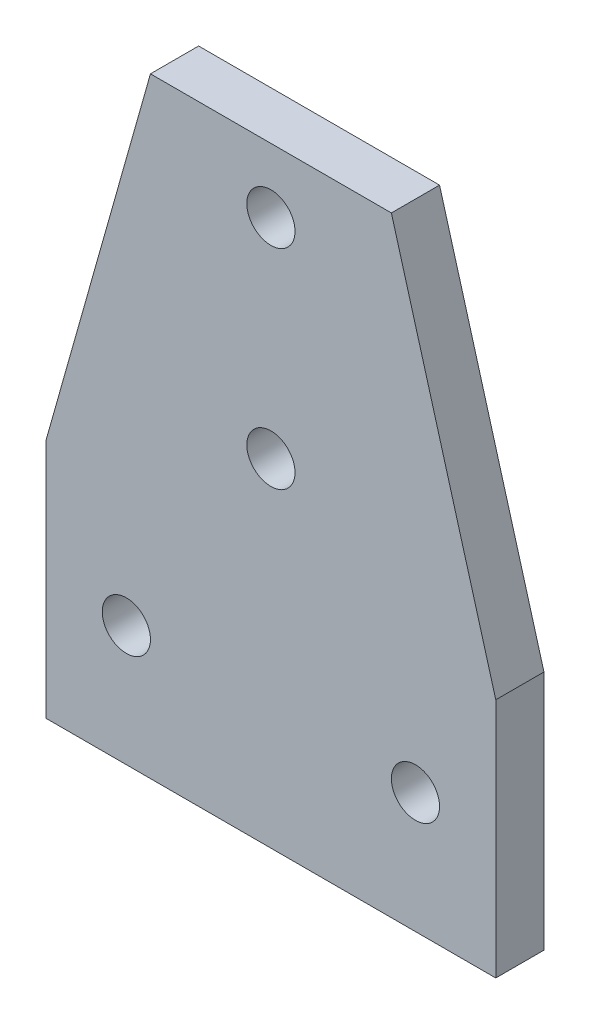
SolidWorks part; units mm, degrees
ref_plane "前视基准面" through (0, 0, 0) normal (0, 0, 1) x (1, 0, 0)
ref_plane "上视基准面" through (0, 0, 0) normal (0, 1, 0) x (1, 0, 0)
ref_plane "右视基准面" through (0, 0, 0) normal (1, 0, 0) x (0, 0, -1)
sketch "草图1" plane through (0, 0, 0) normal (0, 0, 1) x (1, 0, 0)
  line L0 (0, 0) -> (15, 0)
  line L2 (32.5, -38) -> (-17.5, -38)
  line L4 (-17.5, -38) -> (-17.5, -23)
  line L5 (-17.5, -23) -> (0, 0)
  line L6 (32.5, -38) -> (32.5, -23)
  line L7 (32.5, -23) -> (15, 0)
  point P3 (7.5, 0)
  point P6 (7.5, -38)
  dimension "D1" = 15
  dimension "D2" = 50
  dimension "D3" = 38
  dimension "D4" = 15
  dimension "D5" = 15
extrude "凸台-拉伸1" add sketch "草图1" along normal blind 3
sketch "草图2" plane through (0, 0, 3) normal (0, 0, 1) x (1, 0, 0)
  line L0 (15, 0) -> (0, 0) construction
  line L1 (32.5, -38) -> (32.5, -23) construction
  line L2 (-17.5, -38) -> (32.5, -38) construction
  circle A0 centre (7.5, -4) radius 1.5
  circle A1 centre (7.5, -17) radius 1.5
  circle A2 centre (28.5, -30.5) radius 1.5
  circle A3 centre (16.5, -30.5) radius 1.5
  circle A4 centre (-1.5, -30.5) radius 1.5
  circle A5 centre (-13.5, -30.5) radius 1.5
  point P18 (0, 0)
  point P19 (7.5, 0)
  point P20 (0, 0)
  dimension "D1" = 3
  dimension "D2" = 4
  dimension "D3" = 13
  dimension "D4" = 4
  dimension "D5" = 12
  dimension "D6" = 18
  dimension "D7" = 12
  dimension "D8" = 7.5
extrude "切除-拉伸1" cut sketch "草图2" against normal blind 3
sketch "草图3" plane through (0, 0, 3) normal (0, 0, 1) x (1, 0, 0)
  line L0 (32.5, -23) -> (15, 0) construction
  line L1 (32.5, -38) -> (21.5, -38)
  line L2 (32.5, -38) -> (32.5, -8.5429)
  line L3 (32.5, -8.5429) -> (21.5, -8.5429)
  line L4 (21.5, -38) -> (21.5, -8.5429)
  dimension "D1" = 11
extrude "切除-拉伸2" cut sketch "草图3" against normal blind 3
sketch "草图4" plane through (0, 0, 3) normal (0, 0, 1) x (1, 0, 0)
  line L0 (0, 0) -> (-17.5, -23) construction
  line L1 (-17.5, -38) -> (-6.5, -38)
  line L2 (-17.5, -38) -> (-17.5, -8.5429)
  line L3 (-17.5, -8.5429) -> (-6.5, -8.5429)
  line L4 (-6.5, -38) -> (-6.5, -8.5429)
  dimension "D1" = 11
extrude "切除-拉伸3" cut sketch "草图4" against normal blind 3
sketch "草图5" plane through (0, 0, 3) normal (0, 0, 1) x (1, 0, 0)
  line L0 (-6.5, -23) -> (-6.5, -8.5429)
  line L1 (-6.5, -38) -> (-6.5, -8.5429) construction
  line L2 (-6.5, -8.5429) -> (0, 0)
  line L3 (0, 0) -> (-6.5, -23)
  line L4 (21.5, -23) -> (21.5, -8.5429)
  line L5 (21.5, -8.5429) -> (21.5, -38) construction
  line L6 (21.5, -8.5429) -> (15, 0)
  line L7 (15, 0) -> (21.5, -23)
  dimension "D1" = 15
  dimension "D2" = 15
extrude "切除-拉伸4" cut sketch "草图5" against normal blind 3
